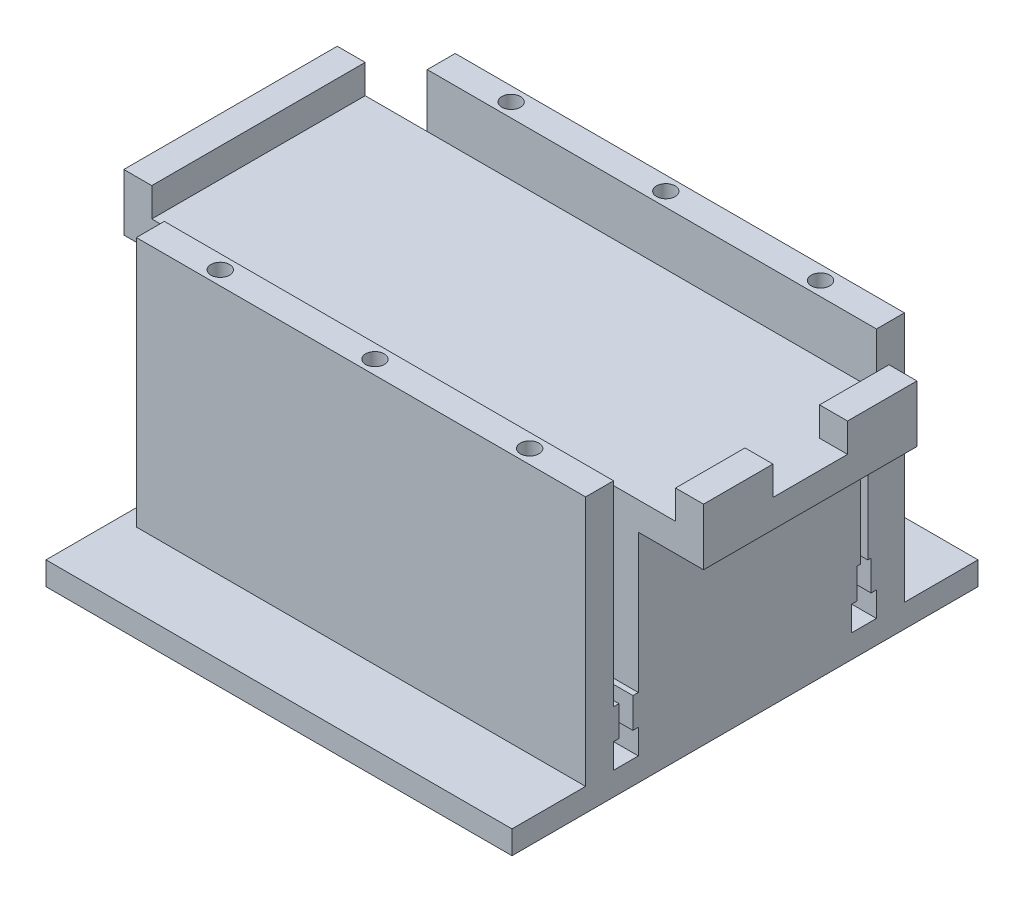
SolidWorks part; units mm, degrees
ref_plane "Front Plane" through (0, 0, 0) normal (0, 0, 1) x (1, 0, 0)
ref_plane "Top Plane" through (0, 0, 0) normal (0, 1, 0) x (1, 0, 0)
ref_plane "Right Plane" through (0, 0, 0) normal (1, 0, 0) x (0, 0, -1)
sketch "Sketch1" plane through (0, 0, 0) normal (0, 1, 0) x (1, 0, 0)
  line L1 (23.2, -12.375) -> (-23.2, -12.375)
  line L2 (23.2, -12.375) -> (23.2, 12.375)
  line L3 (23.2, 12.375) -> (-23.2, 12.375)
  line L4 (-23.2, -12.375) -> (-23.2, 12.375)
  line L5 (23.2, -12.375) -> (-23.2, 12.375) construction
  line L6 (23.2, 12.375) -> (-23.2, -12.375) construction
  point P0 (0, 0)
  dimension "D1" = 24.75
  dimension "D2" = 46.4
extrude "Boss-Extrude1" add sketch "Sketch1" along normal blind 5.9
sketch "Sketch2" plane through (0, 5.9, 0) normal (0, 1, 0) x (1, 0, 0)
  line L0 (23.2, 0) -> (23.2, 11.45)
  line L1 (23.2, -12.375) -> (23.2, 12.375) construction
  line L2 (23.2, 0) -> (23.2, -11.45)
  line L3 (23.2, -11.45) -> (23.2, 11.45)
  line L4 (23.2, -11.45) -> (-23.2, -11.45)
  line L5 (23.2, 11.45) -> (-23.2, 11.45)
  line L6 (-23.2, -11.45) -> (-23.2, 11.45)
  line M4 (-23.2, 12.375) -> (-23.2, -12.375)
  line M6 (23.2, -12.375) -> (23.2, 12.375)
  dimension "D1" = 11.45
  dimension "D2" = 11.45
  dimension "D3" = 46.4
extrude "Boss-Extrude2" add sketch "Sketch2" along normal blind 2.5 contours L5 L4 M6 M4
sketch "Sketch3" plane through (0, 0, 0) normal (0, -1, 0) x (1, 0, 0)
  line L1 (-25, 25) -> (25, 25)
  line L2 (-25, 25) -> (-25, -25)
  line L3 (-25, -25) -> (25, -25)
  line L4 (25, 25) -> (25, -25)
  line L5 (-25, 25) -> (25, -25) construction
  line L6 (-25, -25) -> (25, 25) construction
  point P0 (0, 0)
  dimension "D1" = 50
  dimension "D2" = 50
extrude "Boss-Extrude3" add sketch "Sketch3" along normal blind 2.5
sketch "Sketch4" plane through (0, 0, 0) normal (0, 1, 0) x (1, 0, 0)
  line L1 (-23.2, 12.375) -> (-23.2, 13.175)
  line L3 (23.2, 12.375) -> (23.2, 13.175)
  line L4 (23.2, 13.175) -> (-23.2, 13.175)
  line L5 (23.2, 13.175) -> (23.2, 15.175)
  line L6 (-23.2, 13.175) -> (-23.2, 15.175)
  line L7 (23.2, 15.175) -> (-23.2, 15.175)
  line L8 (23.2, 13.175) -> (-23.2, 13.175)
  line L9 (23.2, 13.175) -> (23.2, 14.105)
  line L10 (-23.2, 13.175) -> (-23.2, 14.105)
  line L11 (23.2, 14.105) -> (-23.2, 14.105)
  dimension "D1" = 0.8
  dimension "D2" = 2
  dimension "D3" = 0.93
extrude "Boss-Extrude4" add sketch "Sketch4" along normal up to surface (5.9 mm away) contours L5 L11 L6 L4 up to face at (0, 5.9, -11.9125)
sketch "Sketch5" plane through (0, 0, 0) normal (0, 1, 0) x (1, 0, 0)
  line L0 (-23.2, -12.375) -> (-23.2, -13.175)
  line L1 (23.2, -12.375) -> (23.2, -13.175)
  line L2 (23.2, -13.175) -> (-23.2, -13.175)
  line L3 (23.2, -13.175) -> (23.2, -14.105)
  line L4 (-23.2, -13.175) -> (-23.2, -14.105)
  line L5 (23.2, -14.105) -> (-23.2, -14.105)
  dimension "D1" = 0.8
  dimension "D2" = 0.93
extrude "Boss-Extrude5" add sketch "Sketch5" along normal up to surface (5.9 mm away) contours L5 L3 L2 L4 up to face at (0, 5.9, 11.9125)
sketch "Sketch6" plane through (0, 0, 0) normal (0, 1, 0) x (1, 0, 0)
  line L0 (-23.2, 14.105) -> (23.2, 14.105)
  line L1 (-23.2, 14.105) -> (-23.2, 17.105)
  line L2 (23.2, 14.105) -> (23.2, 17.105)
  line L3 (-23.2, 17.105) -> (23.2, 17.105)
  dimension "D1" = 3
extrude "Boss-Extrude6" add sketch "Sketch6" along normal up to surface (8.4 mm away) up to face at (0, 8.4, 0)
sketch "Sketch7" plane through (0, 0, 0) normal (0, 1, 0) x (1, 0, 0)
  line L0 (23.2, -14.105) -> (-23.2, -14.105)
  line L1 (23.2, -14.105) -> (23.2, -17.105)
  line L2 (-23.2, -14.105) -> (-23.2, -17.105)
  line L3 (23.2, -17.105) -> (-23.2, -17.105)
  dimension "D1" = 3
extrude "Boss-Extrude7" add sketch "Sketch7" along normal up to surface (8.4 mm away) up to face at (0, 8.4, 0)
sketch "Sketch8" plane through (0, 8.4, 0) normal (0, 1, 0) x (1, 0, 0)
  line L0 (-23.2, 11.45) -> (-23.2, -11.45)
  line L1 (-23.2, 11.45) -> (23.2, 11.45)
  line L2 (-23.2, -11.45) -> (23.2, -11.45)
  line L3 (23.2, 11.45) -> (23.2, -11.45)
  line L4 (23.2, -11.45) -> (23.2, 11.45) construction
  dimension "D1" = 0
extrude "Boss-Extrude8" add sketch "Sketch8" along normal blind 8.4
sketch "Sketch9" plane through (0, 8.4, 0) normal (0, 1, 0) x (1, 0, 0)
  line L0 (-23.2, -14.105) -> (-23.2, -17.105)
  line L1 (-23.2, -14.105) -> (23.2, -14.105)
  line L2 (-23.2, -17.105) -> (23.2, -17.105)
  line L3 (23.2, -14.105) -> (23.2, -17.105)
  line L4 (23.2, -17.105) -> (23.2, -14.105) construction
  dimension "D1" = 0
extrude "Boss-Extrude9" add sketch "Sketch9" along normal blind 8.4
sketch "Sketch10" plane through (23.2, 0, 0) normal (1, 0, 0) x (0, 0, -1)
  line L0 (-11.45, 16.8) -> (-11.45, 5.9)
  line L1 (-11.45, 16.8) -> (11.45, 16.8)
  line L2 (-11.45, 5.9) -> (11.45, 5.9)
  line L3 (11.45, 16.8) -> (11.45, 5.9)
  line L4 (-12.375, 5.9) -> (-12.375, 0)
  line L5 (-12.375, 5.9) -> (12.375, 5.9)
  line L6 (-12.375, 0) -> (12.375, 0)
  line L7 (12.375, 5.9) -> (12.375, 0)
  line L8 (12.375, 5.9) -> (12.375, 0) construction
  line L9 (11.45, 16.8) -> (11.45, 5.9) construction
  line M3 (-12.375, 0) -> (12.375, 0)
  line M4 (12.375, 0) -> (12.375, 5.9)
  line M5 (12.375, 5.9) -> (11.45, 5.9)
  line M6 (11.45, 5.9) -> (11.45, 16.8)
  line M7 (11.45, 16.8) -> (-11.45, 16.8)
  line M8 (-11.45, 16.8) -> (-11.45, 5.9)
  line M9 (-11.45, 5.9) -> (-12.375, 5.9)
  line M10 (-12.375, 5.9) -> (-12.375, 0)
  dimension "D1" = 0
  dimension "D2" = 0
extrude "Boss-Extrude10" add sketch "Sketch10" along normal up to surface (1.8 mm away) contours L2 M8 M6 M7 | L2 M9 M10 M3 M4 M5 up to face at (25, -1.25, 0)
sketch "Sketch11" plane through (23.2, 0, 0) normal (1, 0, 0) x (0, 0, -1)
  line L0 (-17.105, 16.8) -> (-14.105, 16.8)
  line L1 (-17.105, 16.8) -> (-17.105, 0)
  line L2 (-14.105, 16.8) -> (-14.105, 0)
  line L3 (-17.105, 0) -> (-14.105, 0)
  line L4 (-13.175, 0) -> (-17.105, 0) construction
  line L5 (-13.175, 5.9) -> (-14.105, 5.9)
  line L6 (-13.175, 5.9) -> (-13.175, 0)
  line L7 (-14.105, 5.9) -> (-14.105, 0)
  line L8 (-13.175, 0) -> (-14.105, 0)
  line M3 (-13.175, 0) -> (-13.175, 5.9)
  line M4 (-13.175, 5.9) -> (-14.105, 5.9)
  line M5 (-14.105, 5.9) -> (-14.105, 16.8)
  line M6 (-14.105, 16.8) -> (-17.105, 16.8)
  line M7 (-17.105, 16.8) -> (-17.105, 0)
  line M8 (-17.105, 0) -> (-13.175, 0)
  dimension "D1" = 0
  dimension "D2" = 0
extrude "Boss-Extrude11" add sketch "Sketch11" along normal up to surface (1.8 mm away) contours L2 M5 M6 M7 M8 | L2 M4 M8 M3 up to face at (25, 4.35, 0)
sketch "Sketch12" plane through (0, 5.9, 0) normal (0, 1, 0) x (1, 0, 0)
  line L0 (-23.2, -11.45) -> (-23.2, -12.375)
  line L1 (-23.2, -11.45) -> (9.5, -11.45)
  line L2 (-23.2, -12.375) -> (9.5, -12.375)
  line L3 (9.5, -11.45) -> (9.5, -12.375)
  line L4 (25, -11.45) -> (25, -12.375) construction
  line L5 (-23.2, -13.175) -> (-23.2, -14.105)
  line L6 (-23.2, -13.175) -> (9.5, -13.175)
  line L7 (-23.2, -14.105) -> (9.5, -14.105)
  line L8 (9.5, -13.175) -> (9.5, -14.105)
  line L9 (25, -14.105) -> (25, -13.175) construction
  dimension "D1" = 15.5
  dimension "D2" = 15.5
extrude "Boss-Extrude12" add sketch "Sketch12" along normal blind 8.4
sketch "Sketch13" plane through (23.2, 0, 0) normal (1, 0, 0) x (0, 0, -1)
  line L0 (17.105, 8.4) -> (14.105, 8.4)
  line L1 (17.105, 8.4) -> (17.105, 0)
  line L2 (14.105, 8.4) -> (14.105, 0)
  line L3 (17.105, 0) -> (14.105, 0)
  line L4 (13.175, 0) -> (17.105, 0) construction
  line L5 (14.105, 5.9) -> (13.175, 5.9)
  line L6 (14.105, 5.9) -> (14.105, 0)
  line L7 (13.175, 5.9) -> (13.175, 0)
  line L8 (14.105, 0) -> (13.175, 0)
  line M3 (14.105, 5.9) -> (13.175, 5.9)
  line M4 (13.175, 5.9) -> (13.175, 0)
  line M5 (13.175, 0) -> (17.105, 0)
  line M6 (17.105, 0) -> (17.105, 8.4)
  line M7 (17.105, 8.4) -> (14.105, 8.4)
  line M8 (14.105, 8.4) -> (14.105, 5.9)
  dimension "D1" = 0
  dimension "D2" = 0
extrude "Boss-Extrude13" add sketch "Sketch13" along normal up to surface (1.8 mm away) contours L2 M8 M5 M6 M7 | L2 M3 M4 M5 up to face at (25, 5.4222, 4.9317)
sketch "Sketch14" plane through (0, 8.4, 0) normal (0, 1, 0) x (1, 0, 0)
  line L0 (-23.2, 17.105) -> (-23.2, 14.105)
  line L1 (-23.2, 17.105) -> (25, 17.105)
  line L2 (-23.2, 14.105) -> (25, 14.105)
  line L3 (25, 17.105) -> (25, 14.105)
  line L4 (25, 14.105) -> (25, 17.105) construction
  dimension "D1" = 0
extrude "Boss-Extrude14" add sketch "Sketch14" along normal blind 8.4
sketch "Sketch15" plane through (0, 5.9, 0) normal (0, 1, 0) x (1, 0, 0)
  line L0 (25, 14.105) -> (25, 13.175)
  line L1 (25, 14.105) -> (-7.7, 14.105)
  line L2 (25, 13.175) -> (-7.7, 13.175)
  line L3 (-7.7, 14.105) -> (-7.7, 13.175)
  line L4 (-23.2, 13.175) -> (-23.2, 14.105) construction
  line L5 (25, 12.375) -> (25, 11.45)
  line L6 (25, 12.375) -> (-7.7, 12.375)
  line L7 (25, 11.45) -> (-7.7, 11.45)
  line L8 (-7.7, 12.375) -> (-7.7, 11.45)
  line L9 (-23.2, 12.375) -> (-23.2, 11.45) construction
  dimension "D1" = 15.5
  dimension "D2" = 15.5
extrude "Boss-Extrude15" add sketch "Sketch15" along normal blind 8.4
sketch "Sketch16" plane through (25, 0, 0) normal (1, 0, 0) x (0, 0, -1)
  line L0 (-12.775, 0) -> (-12.025, 0)
  line L1 (-12.375, 0) -> (-13.175, 0) construction
  line L2 (-12.775, 0) -> (-13.525, 0)
  line L3 (-12.025, 0) -> (-13.525, 0)
  line L4 (-12.025, 0) -> (-12.025, 5.9)
  line L5 (-13.525, 0) -> (-13.525, 5.9)
  line L6 (-12.025, 5.9) -> (-13.525, 5.9)
  line L7 (-11.45, 5.9) -> (-12.375, 5.9) construction
  line M15 (-11.45, 5.9) -> (-12.375, 5.9)
  line M16 (-12.375, 5.9) -> (-12.375, 0)
  line M18 (-13.175, 0) -> (-13.175, 5.9)
  line M19 (-13.175, 5.9) -> (-14.105, 5.9)
  dimension "D1" = 0.75
  dimension "D2" = 0
extrude "Cut-Extrude1" cut sketch "Sketch16" against normal through all contours L0 L4 M15 M16 | L5 L2 M18 M19
sketch "Sketch18" plane through (25, 0, 0) normal (1, 0, 0) x (0, 0, -1)
  line L0 (12.775, 0) -> (13.525, 0)
  line L1 (13.175, 0) -> (12.375, 0) construction
  line L2 (12.775, 0) -> (12.025, 0)
  line L3 (12.025, 0) -> (13.525, 0)
  line L4 (12.025, 0) -> (12.025, 5.9)
  line L5 (13.525, 0) -> (13.525, 5.9)
  line L6 (12.025, 5.9) -> (13.525, 5.9)
  line L7 (12.375, 5.9) -> (11.45, 5.9) construction
  line M19 (13.175, 14.3) -> (13.175, 0)
  line M21 (12.375, 0) -> (12.375, 14.3)
  dimension "D1" = 0.75
  dimension "D2" = 0
extrude "Cut-Extrude2" cut sketch "Sketch18" against normal through all contours L6 L4 L2 M21 | L6 L0 L5 M19
sketch "Sketch20" plane through (-23.2, 0, 0) normal (-1, 0, 0) x (0, 0, 1)
  line L0 (11.45, 16.8) -> (11.45, 14.3)
  line L1 (11.45, 16.8) -> (-11.45, 16.8)
  line L2 (11.45, 14.3) -> (-11.45, 14.3)
  line L3 (-11.45, 16.8) -> (-11.45, 14.3)
  line L4 (-11.45, 16.8) -> (-11.45, 5.9) construction
  dimension "D1" = 0
extrude "Boss-Extrude17" add sketch "Sketch20" along normal blind 4
sketch "Sketch22" plane through (-27.2, 0, 0) normal (-1, 0, 0) x (0, 0, 1)
  line L0 (11.45, 16.8) -> (11.45, 14.3)
  line L1 (11.45, 16.8) -> (-11.45, 16.8)
  line L2 (11.45, 14.3) -> (-11.45, 14.3)
  line L3 (-11.45, 16.8) -> (-11.45, 14.3)
  line L4 (-11.45, 16.8) -> (-11.45, 14.3) construction
  dimension "D1" = 0
extrude "Boss-Extrude19" add sketch "Sketch22" along normal blind 3
sketch "Sketch23" plane through (0, 16.8, 0) normal (0, 1, 0) x (1, 0, 0)
  line L0 (-30.2, -11.45) -> (-30.2, 11.45)
  line L1 (-30.2, -11.45) -> (-27.2, -11.45)
  line L2 (-30.2, 11.45) -> (-27.2, 11.45)
  line L3 (-27.2, -11.45) -> (-27.2, 11.45)
  dimension "D1" = 3
extrude "Boss-Extrude20" add sketch "Sketch23" along normal blind 1.5
sketch "Sketch24" plane through (25, 0, 0) normal (1, 0, 0) x (0, 0, -1)
  line L0 (11.45, 16.8) -> (11.45, 14.3)
  line L1 (11.45, 16.8) -> (-11.45, 16.8)
  line L2 (11.45, 14.3) -> (-11.45, 14.3)
  line L3 (-11.45, 16.8) -> (-11.45, 14.3)
  line L4 (-11.45, 5.9) -> (-11.45, 16.8) construction
  dimension "D1" = 0
extrude "Boss-Extrude21" add sketch "Sketch24" along normal blind 7
sketch "Sketch25" plane through (0, 16.8, 0) normal (0, 1, 0) x (1, 0, 0)
  line L0 (32, -11.45) -> (29, -11.45)
  line L1 (32, -11.45) -> (32, 11.45)
  line L2 (29, -11.45) -> (29, 11.45)
  line L3 (32, 11.45) -> (29, 11.45)
  line L4 (-27.2, -11.45) -> (32, -11.45) construction
  line L5 (32, 11.45) -> (-27.2, 11.45) construction
  dimension "D1" = 3
  dimension "D2" = 0
extrude "Boss-Extrude22" add sketch "Sketch25" along normal blind 3
sketch "Sketch27" plane through (0, 16.8, 0) normal (0, 1, 0) x (1, 0, 0)
  line L0 (25, 17.105) -> (25, 14.105)
  line L1 (25, 17.105) -> (-23.2, 17.105)
  line L2 (25, 14.105) -> (-23.2, 14.105)
  line L3 (-23.2, 17.105) -> (-23.2, 14.105)
  line L4 (-23.2, 17.105) -> (-23.2, 14.105) construction
  line L5 (25, -14.105) -> (25, -17.105)
  line L6 (25, -14.105) -> (-23.2, -14.105)
  line L7 (25, -17.105) -> (-23.2, -17.105)
  line L8 (-23.2, -14.105) -> (-23.2, -17.105)
  line L9 (-23.2, -14.105) -> (-23.2, -17.105) construction
  dimension "D1" = 0
  dimension "D2" = 0
extrude "Boss-Extrude23" add sketch "Sketch27" along normal blind 7
sketch "Sketch28" plane through (0, 16.8, 0) normal (0, 1, 0) x (1, 0, 0)
  line L0 (29, 11.45) -> (29, -11.45)
  line L1 (29, 11.45) -> (-27.2, 11.45)
  line L2 (29, -11.45) -> (-27.2, -11.45)
  line L3 (-27.2, 11.45) -> (-27.2, -11.45)
  line L4 (-27.2, -11.45) -> (-27.2, 11.45) construction
  dimension "D1" = 0
extrude "Boss-Extrude24" add sketch "Sketch28" along normal blind 7
sketch "Sketch29" plane through (0, 18.3, 0) normal (0, 1, 0) x (1, 0, 0)
  line L0 (-30.2, 11.45) -> (-27.2, 11.45)
  line L1 (-30.2, 11.45) -> (-30.2, -11.45)
  line L2 (-27.2, 11.45) -> (-27.2, -11.45)
  line L3 (-30.2, -11.45) -> (-27.2, -11.45)
  line L4 (-30.2, -11.45) -> (-27.2, -11.45) construction
  point P8 (-28.7, -11.45)
  dimension "D1" = 0
extrude "Boss-Extrude25" add sketch "Sketch29" along normal blind 7
sketch "Sketch30" plane through (0, 19.8, 0) normal (0, 1, 0) x (1, 0, 0)
  line L0 (32, 11.45) -> (29, 11.45)
  line L1 (32, 11.45) -> (32, -11.45)
  line L2 (29, 11.45) -> (29, -11.45)
  line L3 (32, -11.45) -> (29, -11.45)
  line L4 (29, -11.45) -> (32, -11.45) construction
  dimension "D1" = 0
extrude "Boss-Extrude26" add sketch "Sketch30" along normal blind 7
sketch "Sketch31" plane through (0, 0, -11.45) normal (0, 0, -1) x (-1, 0, 0)
  line L0 (30.2, 14.3) -> (23.2, 14.3)
  line L1 (30.2, 14.3) -> (30.2, 20.8)
  line L2 (23.2, 14.3) -> (23.2, 20.8)
  line L3 (30.2, 20.8) -> (23.2, 20.8)
  line L4 (-29, 23.8) -> (27.2, 23.8) construction
  dimension "D1" = 3
extrude "Cut-Extrude3" cut sketch "Sketch31" against normal through all
sketch "Sketch32" plane through (0, 0, 11.45) normal (0, 0, 1) x (1, 0, 0)
  line L0 (25, 14.3) -> (32, 14.3)
  line L1 (25, 14.3) -> (25, 20.8)
  line L2 (32, 14.3) -> (32, 20.8)
  line L3 (25, 20.8) -> (32, 20.8)
  line L4 (-27.2, 23.8) -> (29, 23.8) construction
  dimension "D1" = 3
extrude "Cut-Extrude4" cut sketch "Sketch32" against normal through all
sketch "Sketch33" plane through (-23.2, 0, 0) normal (-1, 0, 0) x (0, 0, 1)
  line L0 (-14.105, 0) -> (-11.445, 0)
  line L1 (-14.105, 0) -> (-14.105, 2.66)
  line L2 (-11.445, 0) -> (-11.445, 2.66)
  line L3 (-14.105, 2.66) -> (-11.445, 2.66)
  line L5 (25, 0) -> (-25, 0) construction
  line L6 (-14.105, 23.8) -> (-14.105, 5.9) construction
  dimension "D1" = 2.66
  dimension "D2" = 2.66
  dimension "D3" = 0
  dimension "D4" = 0
extrude "Cut-Extrude5" cut sketch "Sketch33" against normal through all
sketch "Sketch34" plane through (-23.2, 0, 0) normal (-1, 0, 0) x (0, 0, 1)
  line L0 (11.445, 0) -> (14.105, 0)
  line L1 (11.445, 0) -> (11.445, 2.66)
  line L2 (14.105, 0) -> (14.105, 2.66)
  line L3 (11.445, 2.66) -> (14.105, 2.66)
  line L4 (25, 0) -> (-25, 0) construction
  line L5 (14.105, 23.8) -> (14.105, 14.3) construction
  dimension "D1" = 2.66
  dimension "D2" = 2.66
  dimension "D3" = 0
  dimension "D4" = 0
extrude "Cut-Extrude6" cut sketch "Sketch34" against normal through all
sketch "Sketch35" plane through (0, 26.8, 0) normal (0, 1, 0) x (1, 0, 0)
  line L0 (29, 11.45) -> (32, 11.45)
  line L1 (29, 11.45) -> (29, -11.45)
  line L2 (32, 11.45) -> (32, -11.45)
  line L3 (29, -11.45) -> (32, -11.45)
  line L4 (29, -11.45) -> (32, -11.45) construction
  line L6 (37.3606, -4) -> (26.6394, -4)
  line L7 (37.3606, -4) -> (37.3606, 4)
  line L8 (37.3606, 4) -> (26.6394, 4)
  line L9 (26.6394, -4) -> (26.6394, 4)
  line L10 (37.3606, -4) -> (26.6394, 4) construction
  line L11 (37.3606, 4) -> (26.6394, -4) construction
  point P8 (32, 0)
  dimension "D1" = 0
  dimension "D2" = 8
extrude "Cut-Extrude7" cut sketch "Sketch35" against normal up to surface (3 mm away) contours L2 L8 L1 L6 up to face at (0.9, 23.8, 0)
sketch "Sketch36" plane through (0, 25.3, 0) normal (0, 1, 0) x (1, 0, 0)
  line L0 (-30.2, 11.45) -> (-27.2, 11.45)
  line L1 (-30.2, 11.45) -> (-30.2, -11.45)
  line L2 (-27.2, 11.45) -> (-27.2, -11.45)
  line L3 (-30.2, -11.45) -> (-27.2, -11.45)
  line L4 (-30.2, -11.45) -> (-27.2, -11.45) construction
  dimension "D1" = 0
extrude "Boss-Extrude27" add sketch "Sketch36" along normal up to surface (1.5 mm away) up to face at (30.5, 26.8, 7.725)
sketch "Sketch38" plane through (0, 23.8, 0) normal (0, 1, 0) x (1, 0, 0)
  line L0 (-23.2, -14.105) -> (-23.2, -17.105)
  line L1 (-23.2, -14.105) -> (25, -14.105)
  line L2 (-23.2, -17.105) -> (25, -17.105)
  line L3 (25, -14.105) -> (25, -17.105)
  line L4 (25, -17.105) -> (25, -14.105) construction
  dimension "D1" = 0
extrude "Boss-Extrude28" add sketch "Sketch38" along normal blind 3.1
sketch "Sketch39" plane through (0, 23.8, 0) normal (0, 1, 0) x (1, 0, 0)
  line L0 (-23.2, 17.105) -> (-23.2, 14.105)
  line L1 (-23.2, 17.105) -> (25, 17.105)
  line L2 (-23.2, 14.105) -> (25, 14.105)
  line L3 (25, 17.105) -> (25, 14.105)
  line L4 (25, 14.105) -> (25, 17.105) construction
  dimension "D1" = 0
extrude "Boss-Extrude29" add sketch "Sketch39" along normal blind 3.1
sketch "Sketch40" plane through (0, 26.8, 0) normal (0, 1, 0) x (1, 0, 0)
  line L0 (29, 4) -> (32, 4)
  line L1 (29, 4) -> (29, 11.45)
  line L2 (32, 4) -> (32, 11.45)
  line L3 (29, 11.45) -> (32, 11.45)
  line L4 (32, 11.45) -> (29, 11.45) construction
  line L5 (32, -11.45) -> (29, -11.45)
  line L6 (32, -11.45) -> (32, -4)
  line L7 (29, -11.45) -> (29, -4)
  line L8 (32, -4) -> (29, -4)
  line L9 (32, -4) -> (29, -4) construction
  dimension "D1" = 0
  dimension "D2" = 0
extrude "Boss-Extrude30" add sketch "Sketch40" along normal blind 0.1
sketch "Sketch41" plane through (0, 26.8, 0) normal (0, 1, 0) x (1, 0, 0)
  line L0 (-30.2, -11.45) -> (-27.2, -11.45)
  line L1 (-30.2, -11.45) -> (-30.2, 11.45)
  line L2 (-27.2, -11.45) -> (-27.2, 11.45)
  line L3 (-30.2, 11.45) -> (-27.2, 11.45)
  line L4 (-30.2, 11.45) -> (-27.2, 11.45) construction
  dimension "D1" = 0
extrude "Boss-Extrude31" add sketch "Sketch41" along normal blind 0.1
sketch "Sketch42" plane through (0, 26.9, 0) normal (0, 1, 0) x (1, 0, 0)
  line L0 (25, 14.105) -> (25, 17.105) construction
  line L1 (-23.2, -17.105) -> (25, -17.105) construction
  line L2 (-23.2, -14.105) -> (-23.2, -17.105) construction
  line L3 (-23.2, 17.105) -> (-23.2, 14.105) construction
  line L4 (25, 17.105) -> (-23.2, 17.105) construction
  line L5 (25, -17.105) -> (25, -14.105) construction
  line L6 (25, -14.105) -> (-23.2, -14.105) construction
  line L7 (-23.2, 14.105) -> (25, 14.105) construction
  circle A0 centre (-15.7, -15.605) radius 1
  circle A1 centre (-15.7, 15.605) radius 1
  circle A2 centre (17.5, -15.605) radius 1
  circle A3 centre (17.5, 15.605) radius 1
  circle A4 centre (0.9, -15.605) radius 1
  circle A5 centre (0.9, 15.605) radius 1
  dimension "D1" = 2
  dimension "D2" = 1.5
  dimension "D4" = 2
  dimension "D5" = 7.5
  dimension "D6" = 1.5
  dimension "D7" = 2
  dimension "D8" = 2
  dimension "D9" = 7.5
  dimension "D10" = 7.5
  dimension "D11" = 33.2
  dimension "D12" = 2
  dimension "D13" = 1.5
  dimension "D14" = 16.6
  dimension "D15" = 2
  dimension "D16" = 16.6
  dimension "D17" = 1.5
  dimension "D3" = 7.5
extrude "Cut-Extrude8" cut sketch "Sketch42" against normal blind 10
